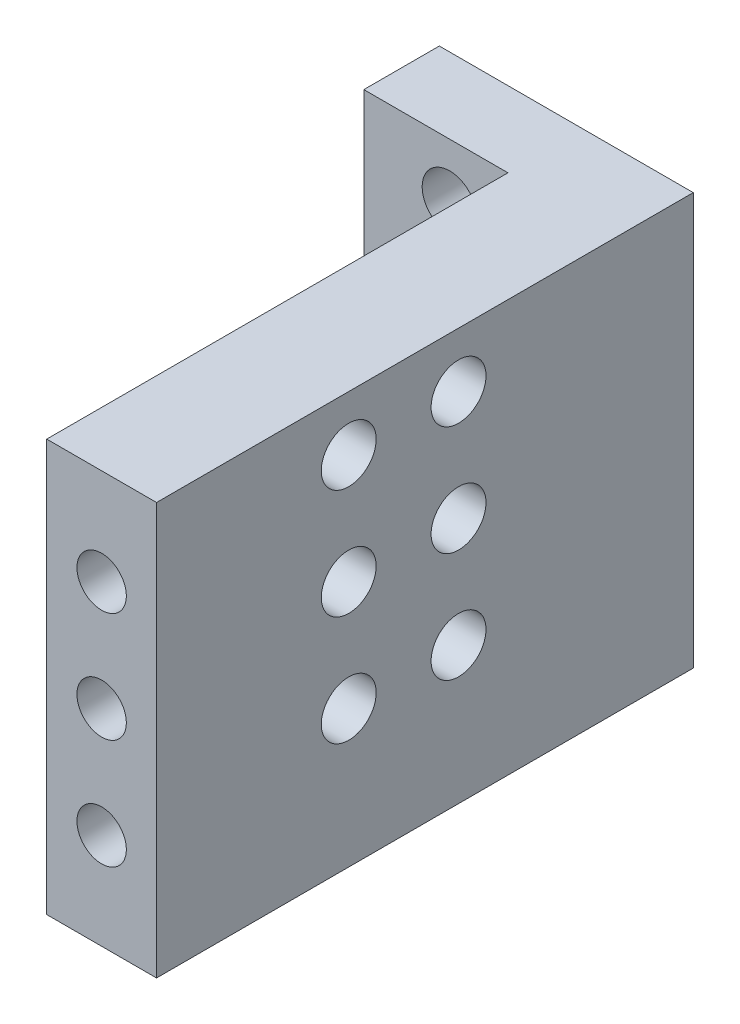
SolidWorks part; units mm, degrees
material "ABS"
ref_plane "前基準面" through (0, 0, 0) normal (0, 0, 1) x (1, 0, 0)
ref_plane "上基準面" through (0, 0, 0) normal (0, 1, 0) x (1, 0, 0)
ref_plane "右基準面" through (0, 0, 0) normal (1, 0, 0) x (0, 0, -1)
sketch "草圖1" plane through (0, 0, 0) normal (0, 1, 0) x (1, 0, 0)
  line L0 (0, 0) -> (0, 33.6)
  line L1 (0, 33.6) -> (-10.5, 33.6)
  line L2 (-10.5, 33.6) -> (-10.5, 39.1)
  line L3 (-10.5, 39.1) -> (8, 39.1)
  line L4 (8, 39.1) -> (8, 0)
  line L5 (8, 0) -> (0, 0)
  dimension "D1" = 39.1
  dimension "D2" = 5.5
  dimension "D3" = 18.5
  dimension "D4" = 8
extrude "填料-伸長1" add sketch "草圖1" along normal blind 30
sketch "草圖2" plane through (0, 0, -39.1) normal (0, 0, -1) x (-1, 0, 0)
  line L0 (10.5, 30) -> (10.5, 0) construction
  line L1 (-8, 0) -> (10.5, 0) construction
  circle A0 centre (4.25, 26) radius 2
  circle A1 centre (4.25, 18) radius 2
  circle A2 centre (4.25, 10) radius 2
  dimension "D1" = 4
  dimension "D2" = 4
  dimension "D3" = 4
  dimension "D4" = 8
  dimension "D5" = 8
  dimension "D6" = 6.25
  dimension "D7" = 10
extrude "除料-伸長1" cut sketch "草圖2" against normal blind 9
sketch "草圖3" plane through (8, 0, 0) normal (1, 0, 0) x (0, 0, -1)
  line L0 (0, 30) -> (0, 0) construction
  line L1 (0, 0) -> (39.1, 0) construction
  circle A0 centre (14, 26) radius 2
  circle A1 centre (14, 18) radius 2
  circle A2 centre (14, 10) radius 2
  circle A3 centre (22, 26) radius 2
  circle A4 centre (22, 18) radius 2
  circle A5 centre (22, 10) radius 2
  dimension "D1" = 4
  dimension "D2" = 8
  dimension "D3" = 8
  dimension "D4" = 14
  dimension "D5" = 10
  dimension "D6" = 2
extrude "除料-伸長2" cut sketch "草圖3" against normal blind 9
sketch "草圖4" plane through (0, 0, 0) normal (0, 0, 1) x (1, 0, 0)
  line L0 (0, 30) -> (0, 0) construction
  line L2 (0, 0) -> (8, 0) construction
  circle A0 centre (4, 23) radius 1.8
  circle A1 centre (4, 15) radius 1.8
  circle A2 centre (4, 7) radius 1.8
  dimension "D5" = 3.6
  dimension "D1" = 8
  dimension "D2" = 8
  dimension "D3" = 4
  dimension "D4" = 7
extrude "除料-伸長3" cut sketch "草圖4" against normal blind 9
